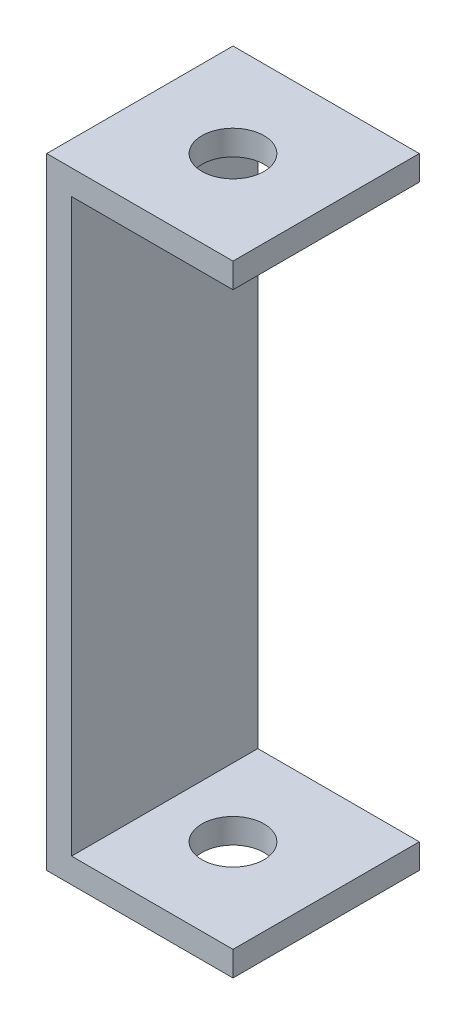
SolidWorks part; units mm, degrees
ref_plane "Alzado" through (0, 0, 0) normal (0, 0, 1) x (1, 0, 0)
ref_plane "Planta" through (0, 0, 0) normal (0, 1, 0) x (1, 0, 0)
ref_plane "Vista lateral" through (0, 0, 0) normal (1, 0, 0) x (0, 0, -1)
sketch "Croquis1" plane through (0, 0, 0) normal (0, 0, 1) x (1, 0, 0)
  line L0 (15, 0) -> (0, 0)
  line L1 (0, 0) -> (0, 50)
  line L2 (0, 50) -> (15, 50)
  line L3 (15, 50) -> (15, 48)
  line L4 (15, 48) -> (2, 48)
  line L5 (2, 48) -> (2, 2)
  line L6 (2, 2) -> (15, 2)
  line L7 (15, 2) -> (15, 0)
  dimension "D1" = 50
  dimension "D2" = 15
  dimension "D3" = 2
  dimension "D4" = 2
extrude "Saliente-Extruir1" add sketch "Croquis1" along normal blind 15
sketch "Croquis2" plane through (0, 50, 0) normal (0, 1, 0) x (1, 0, 0)
  line L1 (15, 0) -> (0, 0) construction
  line L2 (0, -15) -> (0, 0) construction
  circle A0 centre (7.5, -7.5) radius 2.5
  point P7 (0, -7.5)
  point P10 (7.5, 0)
  dimension "D1" = 5
extrude "Cortar-Extruir1" cut sketch "Croquis2" against normal through all
